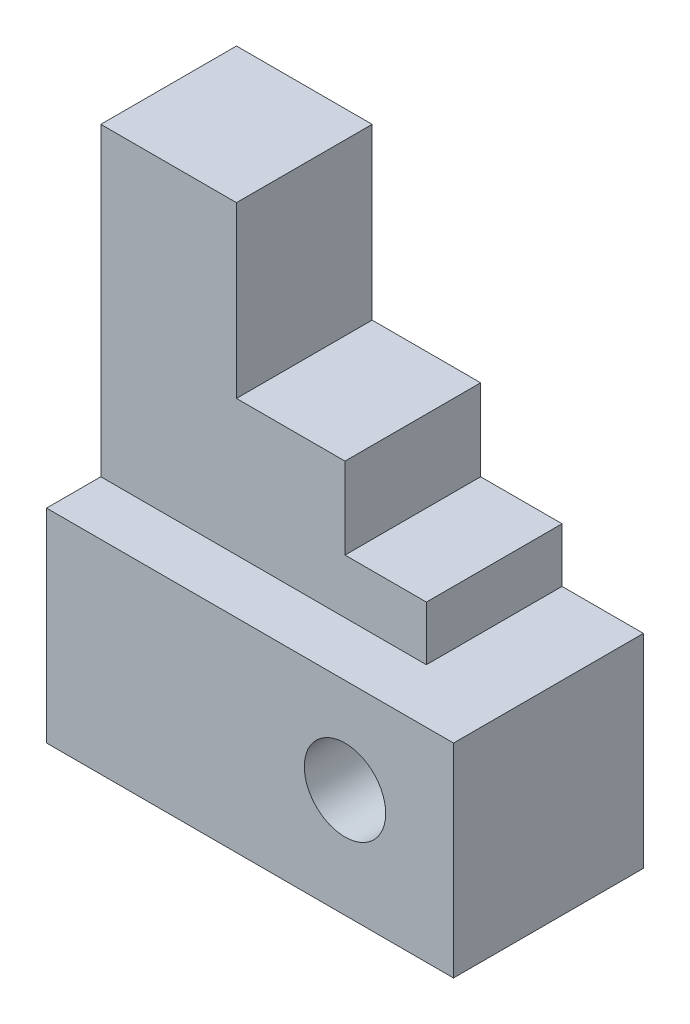
SolidWorks part; units mm, degrees
ref_plane "Płaszczyzna przednia" through (0, 0, 0) normal (0, 0, 1) x (1, 0, 0)
ref_plane "Płaszczyzna górna" through (0, 0, 0) normal (0, 1, 0) x (1, 0, 0)
ref_plane "Płaszczyzna prawa" through (0, 0, 0) normal (1, 0, 0) x (0, 0, -1)
sketch "Szkic2" plane through (0, 0, 0) normal (0, 0, 1) x (1, 0, 0)
  line L1 (0, 0) -> (60, 0)
  line L2 (0, 0) -> (0, 30)
  line L3 (0, 30) -> (60, 30)
  line L4 (60, 0) -> (60, 30)
  circle A0 centre (44, 16) radius 6
  dimension "D3" = 12
  dimension "D1" = 30
  dimension "D2" = 60
  dimension "D4" = 16
  dimension "D5" = 16
extrude "Dodanie-wyciągnięcie1" add sketch "Szkic2" along normal blind 28
sketch "Szkic4" plane through (0, 0, 0) normal (0, 0, 1) x (1, 0, 0)
  line L0 (0, 30) -> (0, 75)
  line L1 (0, 75) -> (20, 75)
  line L2 (20, 75) -> (20, 50)
  line L3 (20, 50) -> (36, 50)
  line L4 (36, 50) -> (36, 38)
  line L5 (36, 38) -> (48, 38)
  line L6 (48, 38) -> (48, 30)
  line L7 (60, 30) -> (0, 30) construction
  line L8 (48, 30) -> (0, 30)
  dimension "D1" = 20
  dimension "D2" = 12
  dimension "D3" = 45
  dimension "D4" = 20
  dimension "D5" = 12
  dimension "D6" = 12
extrude "Dodanie-wyciągnięcie2" add sketch "Szkic4" along normal blind 20
